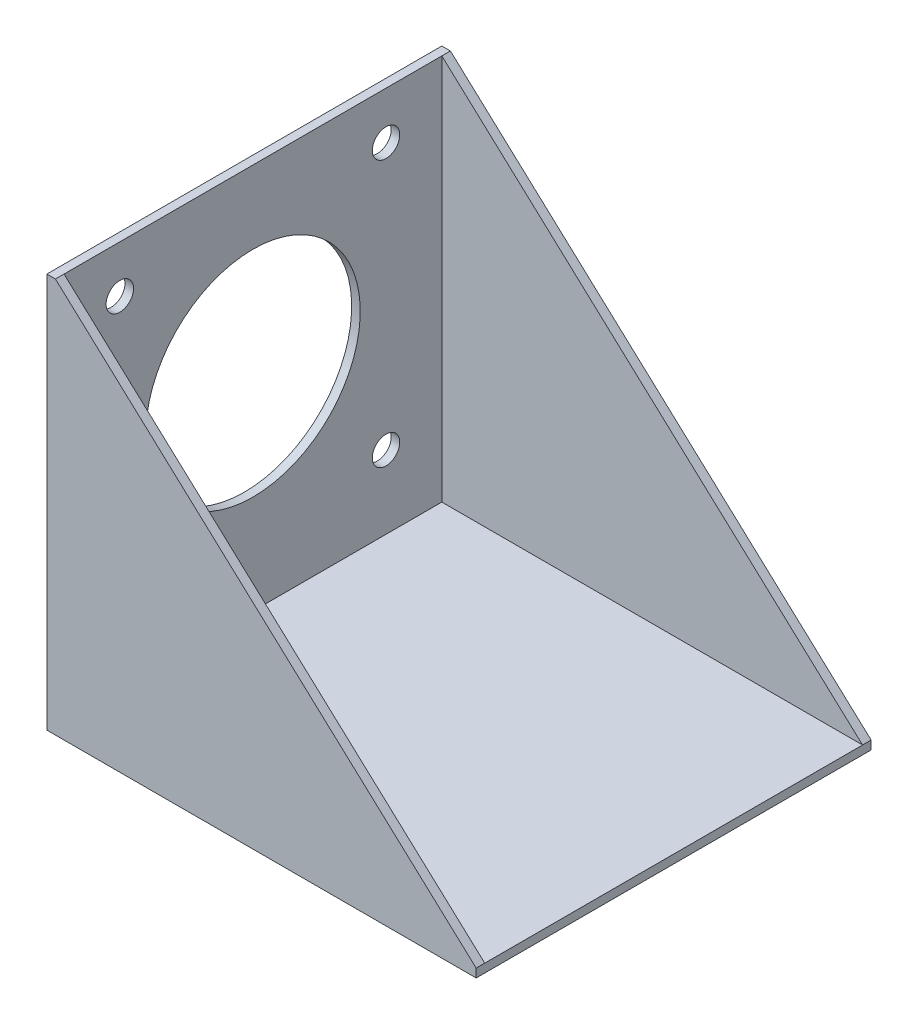
SolidWorks part; units mm, degrees
ref_plane "前视基准面" through (0, 0, 0) normal (0, 0, 1) x (1, 0, 0)
ref_plane "上视基准面" through (0, 0, 0) normal (0, 1, 0) x (1, 0, 0)
ref_plane "右视基准面" through (0, 0, 0) normal (1, 0, 0) x (0, 0, -1)
sketch "草图2" plane through (0, 0, 0) normal (0, 0, 1) x (1, 0, 0)
  line L0 (0, 46) -> (0, 0)
  line L1 (0, 0) -> (50, 0)
  line L2 (1, 46) -> (1, 1)
  line L3 (1, 1) -> (50, 1)
  line L4 (1, 46) -> (0, 46)
  line L5 (50, 0) -> (50, 1)
  dimension "D2" = 46
  dimension "D3" = 50
  dimension "D1" = 1
extrude "凸台-拉伸1" add sketch "草图2" along normal blind 46
sketch "草图3" plane through (0, 0, 46) normal (0, 0, 1) x (1, 0, 0)
  line L0 (1, 46) -> (50, 1)
  line L1 (50, 1) -> (1, 1)
  line L2 (1, 1) -> (1, 46)
extrude "凸台-拉伸2" add sketch "草图3" against normal blind 1
sketch "草图4" plane through (0, 0, 0) normal (0, 0, -1) x (-1, 0, 0)
  line L0 (-1, 46) -> (-50, 1)
  line L1 (-50, 1) -> (-1, 1)
  line L2 (-1, 1) -> (-50, 1) construction
  line L3 (-50, 1) -> (-1, 1) construction
  line L4 (-1, 1) -> (-1, 46)
extrude "凸台-拉伸3" add sketch "草图4" against normal blind 1
sketch "草图5" plane through (0, 0, 0) normal (-1, 0, 0) x (0, 0, 1)
  line L0 (46, 46) -> (0, 46) construction
  line L1 (23, 46) -> (23, 12.8182) construction
  line L2 (-6.5012, 25) -> (54.0279, 25) construction
  circle A0 centre (7.5, 40.5) radius 1.6
  circle A1 centre (38.5, 40.5) radius 1.6
  circle A2 centre (7.5, 9.5) radius 1.6
  circle A3 centre (38.5, 9.5) radius 1.6
  circle A4 centre (23, 25) radius 12.5
  dimension "D1" = 5.5
  dimension "D2" = 31
  dimension "D3" = 3.2
  dimension "D4" = 25
  dimension "D5" = 31
extrude "切除-拉伸1" cut sketch "草图5" against normal blind 1
